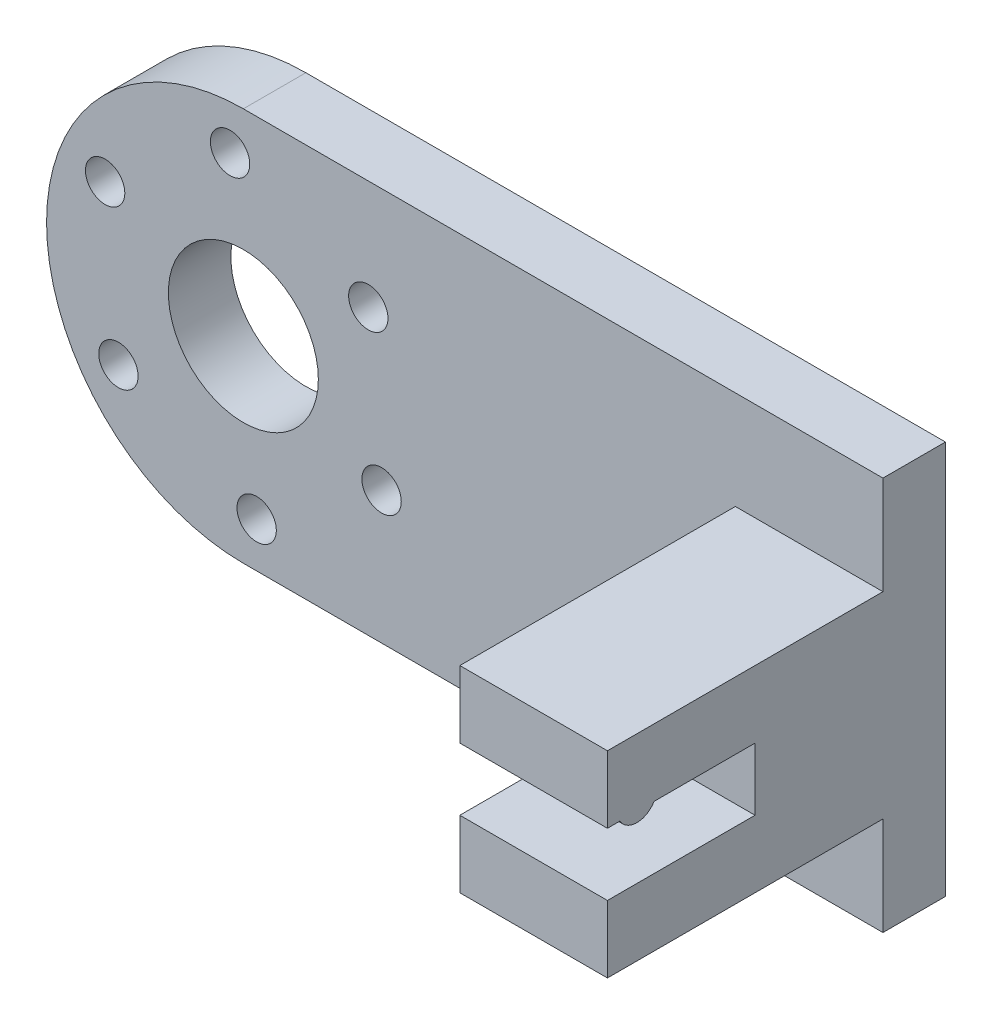
SolidWorks part; units mm, degrees
ref_plane "Front Plane" through (0, 0, 0) normal (0, 0, 1) x (1, 0, 0)
ref_plane "Top Plane" through (0, 0, 0) normal (0, 1, 0) x (1, 0, 0)
ref_plane "Right Plane" through (0, 0, 0) normal (1, 0, 0) x (0, 0, -1)
sketch "Sketch1" plane through (0, 0, 0) normal (0, 0, 1) x (1, 0, 0)
  line L1 (0, 20) -> (65, 20)
  line L2 (0, 20) -> (0, -20)
  line L3 (0, -20) -> (65, -20)
  line L4 (65, 20) -> (65, -20)
  circle A0 centre (0, 0) radius 20
  dimension "D1" = 40
  dimension "D2" = 65
extrude "Boss-Extrude1" add sketch "Sketch1" along normal blind 6.35 contours L2 L1 L4 L3 | A0
sketch "Sketch2" plane through (0, 0, 6.35) normal (0, 0, 1) x (1, 0, 0)
  line L0 (0, 0) -> (0, 15.5) construction
  line L1 (0, 0) -> (-1.3509, 15.441) construction
  line L2 (0, 0) -> (1.3509, -15.441) construction
  circle A0 centre (0, 0) radius 7.62
  circle A1 centre (0, 0) radius 15.5 construction
  circle A2 centre (-1.3509, 15.441) radius 2
  circle A3 centre (12.6969, 8.8904) radius 2
  circle A4 centre (14.0478, -6.5506) radius 2
  circle A5 centre (1.3509, -15.441) radius 2
  circle A6 centre (-12.6969, -8.8904) radius 2
  circle A7 centre (-14.0478, 6.5506) radius 2
  point P20 (0, 0)
  dimension "D1" = 15.24
  dimension "D2" = 31
  dimension "D4" = 4
  dimension "D3" = 5
  dimension "D5" = 6
extrude "Cut-Extrude1" cut sketch "Sketch2" against normal through all
ref_plane "Plane1" through (0, 0, 0) normal (0, 1, 0) x (1, 0, 0)
sketch "Sketch4" plane through (0, 0, 0) normal (0, 1, 0) x (1, 0, 0)
  line L1 (65, -6.35) -> (50, -6.35)
  line L2 (65, -6.35) -> (65, -34.35)
  line L3 (65, -34.35) -> (50, -34.35)
  line L4 (50, -6.35) -> (50, -34.35)
  dimension "D1" = 15
  dimension "D2" = 28
extrude "Boss-Extrude2" add sketch "Sketch4" along normal mid plane 20
sketch "Sketch5" plane through (65, 0, 0) normal (1, 0, 0) x (0, 0, -1)
  line L0 (-34.35, 10) -> (-34.35, -10) construction
  line L1 (-34.35, 3.175) -> (-19.35, 3.175)
  line L2 (-34.35, 3.175) -> (-34.35, -3.175)
  line L3 (-34.35, -3.175) -> (-19.35, -3.175)
  line L4 (-19.35, 3.175) -> (-19.35, -3.175)
  line L5 (0, 0) -> (-34.35, 0) construction
  line L6 (20.3625, 0) -> (-20.3625, 0) construction
  point P11 (-19.35, 0)
  dimension "D1" = 6.35
  dimension "D2" = 15
extrude "Cut-Extrude2" cut sketch "Sketch5" against normal up to next
sketch "Sketch6" plane through (0, 0, 0) normal (0, 0, -1) x (-1, 0, 0)
  line L0 (-65, 0) -> (0, 0) construction
  line L1 (-65, 20) -> (-65, -20) construction
  line L2 (-47.3933, 2.55) -> (-44.0467, 2.55)
  arc A0 (-47.3933, 2.55) -> (-44.0467, 2.55) centre (-45.72, 0) ccw
  point P9 (-45.72, -3.05)
  dimension "D1" = 6.1
  dimension "D2" = 45.72
  dimension "D3" = 5.6
extrude "Cut-Extrude3" cut sketch "Sketch6" against normal up to next
sketch "Sketch7" plane through (0, 0, 0) normal (0, 0, -1) x (-1, 0, 0)
  line L0 (-45.72, 13.5) -> (-45.72, 17.5) construction
  circle A0 centre (-45.72, 0) radius 15.5 construction
  arc A1 (-47.3933, 2.55) -> (-44.0467, 2.55) centre (-45.72, 0) ccw construction
  circle A2 centre (-45.72, 0) radius 13.5
  circle A3 centre (-45.72, 0) radius 17.5
  point P9 (-45.72, 15.5)
  dimension "D1" = 31
  dimension "D2" = 4
extrude "Cut-Extrude4" cut sketch "Sketch7" against normal blind 2
sketch "Sketch8" plane through (65, 0, 0) normal (1, 0, 0) x (0, 0, -1)
  line L1 (-19.35, 3.175) -> (-34.35, 3.175) construction
  line L2 (-34.35, 10) -> (-34.35, 3.175) construction
  circle A0 centre (-31.35, 4.175) radius 2
  point P2 (-31.35, 3.9626)
  dimension "D1" = 4
  dimension "D2" = 3
  dimension "D3" = 1
extrude "Boss-Extrude3" add sketch "Sketch8" against normal up to surface (15 mm away) up to face at (50, 0, 23.6)
